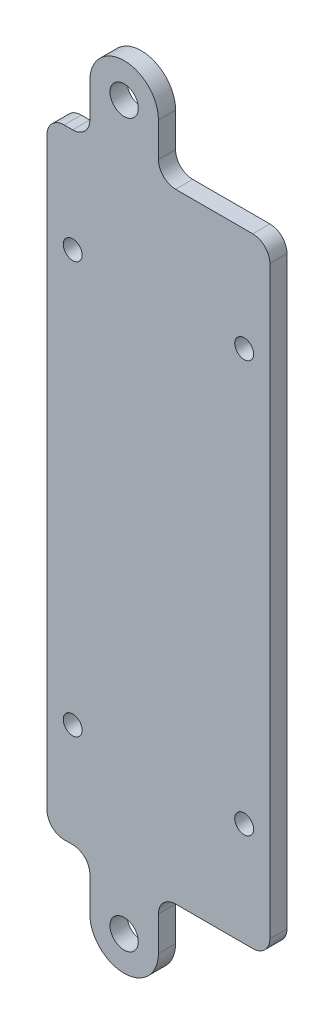
SolidWorks part; units mm, degrees
material "Thornel Mat VMA"
ref_plane "前视基准面" through (0, 0, 0) normal (0, 0, 1) x (1, 0, 0)
ref_plane "上视基准面" through (0, 0, 0) normal (0, 1, 0) x (1, 0, 0)
ref_plane "右视基准面" through (0, 0, 0) normal (1, 0, 0) x (0, 0, -1)
sketch "草图1" plane through (0, 0, 0) normal (0, 0, 1) x (1, 0, 0)
  line L1 (13, -36.1) -> (-13, -36.1)
  line L2 (13, -36.1) -> (13, 36.1)
  line L3 (13, 36.1) -> (-13, 36.1)
  line L4 (-13, -36.1) -> (-13, 36.1)
  line L5 (13, -36.1) -> (-13, 36.1) construction
  line L6 (13, 36.1) -> (-13, -36.1) construction
  line L7 (10, -24) -> (-10, -24) construction
  line L8 (10, -24) -> (10, 24) construction
  line L9 (10, 24) -> (-10, 24) construction
  line L10 (-10, -24) -> (-10, 24) construction
  line L11 (10, -24) -> (-10, 24) construction
  line L12 (10, 24) -> (-10, -24) construction
  circle A0 centre (-10, 24) radius 1.1
  circle A1 centre (10, 24) radius 1.1
  circle A2 centre (-10, -24) radius 1.1
  circle A3 centre (10, -24) radius 1.1
  point P0 (0, 0)
  point P5 (0, 0)
  dimension "D5" = 2.2
  dimension "D6" = 2.2
  dimension "D7" = 2.2
  dimension "D8" = 2.2
  dimension "D1" = 48
  dimension "D2" = 20
  dimension "D3" = 72.2
  dimension "D4" = 26
extrude "凸台-拉伸1" add sketch "草图1" along normal blind 2
sketch "草图2" plane through (0, 0, 2) normal (0, 0, 1) x (1, 0, 0)
  line L0 (-4, 42.1) -> (-4, -42.1) construction
  line L1 (-8, 42.1) -> (-8, 36.1)
  line L2 (-13, -36.1) -> (13, -36.1) construction
  line L3 (0, 42.1) -> (0, 36.1)
  line L4 (-8, -42.1) -> (-8, -36.1)
  line L6 (13, 36.1) -> (-13, 36.1) construction
  line L7 (0, 36.1) -> (-8, 36.1)
  line L8 (0, -42.1) -> (0, -36.1)
  line L11 (0, -36.1) -> (-8, -36.1)
  circle A0 centre (-4, 42.1) radius 1.65
  circle A1 centre (-4, -42.1) radius 1.65
  arc A2 (0, 42.1) -> (-8, 42.1) centre (-4, 42.1) ccw
  arc A3 (-8, -42.1) -> (0, -42.1) centre (-4, -42.1) ccw
  dimension "D1" = 6
  dimension "D2" = 6
  dimension "D3" = 3.3
  dimension "D4" = 3.3
  dimension "D5" = 8
  dimension "D6" = 8
  dimension "D7" = 4
extrude "凸台-拉伸2" add sketch "草图2" against normal up to surface (2 mm away) up to face at (0, 0, 0)
fillet "圆角1" radius 2 8 edges at (-8, 36.1, 1) (-13, 36.1, 1) (0, 36.1, 1) (13, 36.1, 1) (13, -36.1, 1) (0, -36.1, 1) (-13, -36.1, 1) (-8, -36.1, 1)
